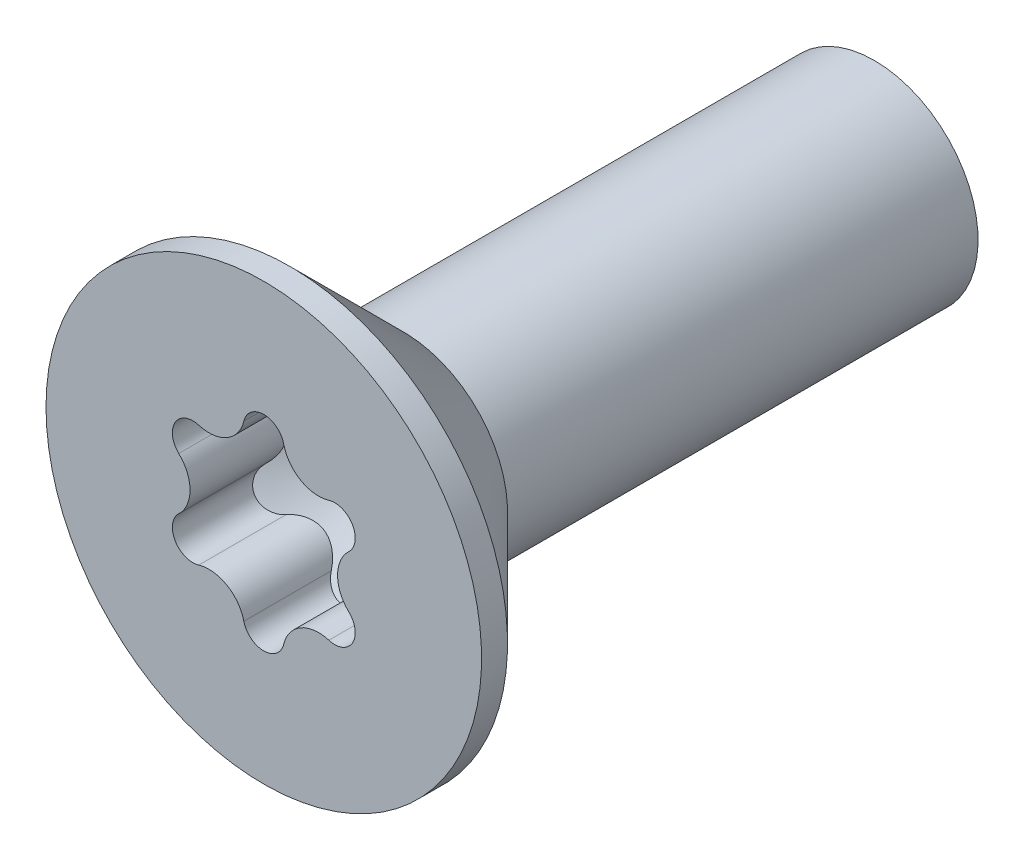
SolidWorks part; units mm, degrees
ref_plane "Front Plane" through (0, 0, 0) normal (0, 0, 1) x (1, 0, 0)
ref_plane "Top Plane" through (0, 0, 0) normal (0, 1, 0) x (1, 0, 0)
ref_plane "Right Plane" through (0, 0, 0) normal (1, 0, 0) x (0, 0, -1)
sketch "BodySke" plane through (0, 0, 0) normal (1, 0, 0) x (0, 0, -1)
  line L0 (0, 0) -> (-1787.2758, 0) construction
  line L1 (0, 0) -> (0, 4.2)
  line L2 (0.5, 4.2) -> (2.7, 2)
  line L3 (0.5, -4.2) -> (2.7, -2) construction
  line L4 (2.7, 2) -> (12, 2)
  line L5 (12, 2) -> (12, 0)
  line L6 (12, 0) -> (0, 0)
  line L7 (0, 0) -> (0, 50000) construction
  line L8 (0.5, 4.2) -> (0, 4.2)
  dimension "D" = 4
  dimension "Dk" = 8.4
  dimension "K" = 2.7
  dimension "L" = 12
  dimension "D1" = 90
  dimension "B" = 12
revolve "Base-Revolve" add sketch "BodySke" angle 360 about L0
cosmetic thread "ThreadCosmetic" [suppressed] parameters "ThdLen"=9.3, "MinorDia"=3.22
sketch "PreBSke" plane through (0, 0, 0) normal (1, 0, 0) x (0, 0, -1)
  line L0 (0, 0) -> (-50000, 0) construction
  line L1 (0, 0) -> (0, 1.975)
  line L2 (0, 4.7) -> (0, -4.7) construction
  line L3 (0, 1.975) -> (1.53, 1.975)
  line L4 (1.53, 1.975) -> (2.7167, 0)
  line L5 (2.7167, 0) -> (0, 0)
  line L6 (1.53, -1.975) -> (2.7167, 0) construction
  dimension "T" = 1.53
  dimension "A" = 3.95
  dimension "D1" = 118
revolve "PreBroach" cut sketch "PreBSke" angle 360 about L0
sketch "HexSke" plane through (0, 0, 0) normal (0, 0, 1) x (1, 0, 0)
  line L0 (0, 0) -> (-43301.2702, 25000) construction
  line L1 (0, 0) -> (-43301.2702, -25000) construction
  line L2 (0, 0) -> (50000, 0) construction
  arc A0 (-1.6394, -0.5027) -> (-1.6394, 0.5027) centre (-2.1139, 0) ccw
  arc A1 (-1.7104, 0.9875) -> (-1.6394, 0.5027) centre (-1.3683, 0.79) ccw
  arc A2 (-1.6394, -0.5027) -> (-1.7104, -0.9875) centre (-1.3683, -0.79) ccw
  arc A3 (-1.2551, 1.1684) -> (-1.7104, 0.9875) centre (-1.3683, 0.79) ccw
  circle A4 centre (0, 0) radius 1.4226 construction
  circle A5 centre (0, 0) radius 1.975 construction
  arc A6 (-1.2551, 1.1684) -> (-0.3843, 1.6711) centre (-1.0569, 1.8307) ccw
  arc A7 (0, 1.975) -> (-0.3843, 1.6711) centre (0, 1.58) ccw
  arc A8 (0.3843, 1.6711) -> (0, 1.975) centre (0, 1.58) ccw
  arc A9 (0.3843, 1.6711) -> (1.2551, 1.1684) centre (1.0569, 1.8307) ccw
  arc A10 (1.7104, 0.9875) -> (1.2551, 1.1684) centre (1.3683, 0.79) ccw
  arc A11 (1.6394, 0.5027) -> (1.7104, 0.9875) centre (1.3683, 0.79) ccw
  arc A12 (1.6394, 0.5027) -> (1.6394, -0.5027) centre (2.1139, 0) ccw
  arc A13 (1.7104, -0.9875) -> (1.6394, -0.5027) centre (1.3683, -0.79) ccw
  arc A14 (1.2551, -1.1684) -> (1.7104, -0.9875) centre (1.3683, -0.79) ccw
  arc A15 (1.2551, -1.1684) -> (0.3843, -1.6711) centre (1.0569, -1.8307) ccw
  arc A16 (0, -1.975) -> (0.3843, -1.6711) centre (0, -1.58) ccw
  arc A17 (-0.3843, -1.6711) -> (0, -1.975) centre (0, -1.58) ccw
  arc A18 (-0.3843, -1.6711) -> (-1.2551, -1.1684) centre (-1.0569, -1.8307) ccw
  arc A19 (-1.7104, -0.9875) -> (-1.2551, -1.1684) centre (-1.3683, -0.79) ccw
  circle A20 centre (0, 0) radius 1.975 construction
  circle A21 centre (0, 0) radius 1.975
  point P56 (0, 0)
  circle M6 centre (0, 0) radius 1.975
  dimension "B" = 2.8452
  dimension "Ri" = 0.395
  dimension "Re" = 0.6913
  dimension "D1" = 60
  dimension "D5" = 6
extrude "Hexalobular" add sketch "HexSke" against normal up to next contours A2 A0 A1 M6 | A7 A3 A6 M6 | A10 A8 A9 M6 | A13 A11 A12 M6 | A16 A14 A15 M6 | A19 A17 A18 M6
sketch "ThdSchSke" plane through (0, 0, 0) normal (1, 0, 0) x (0, 0, -1)
  line L0 (12.2252, 2) -> (12, 1.61)
  line L1 (12, 1.61) -> (11.7748, 2)
  line L2 (11.7748, 2) -> (12.2252, 2)
  line L3 (12, 1.61) -> (12, 2) construction
  line L4 (12, -2) -> (12, 2) construction
  line L5 (12, 2) -> (2.7, 2) construction
  line L6 (0, 0) -> (-50000, 0) construction
  dimension "MinorDia" = 3.22
  dimension "D1" = 60
  dimension "D2" = 0.4503
revolve "ThreadSchematic" cut sketch "ThdSchSke" angle 360 about L6
ref_plane "ThreadPlane" through (0, 0, -2.7) normal (0, 0, -1) x (-1, 0, 0)
pattern_linear "ThdSchPat" [suppressed] count 11
equation "\"MinorDia@ThreadCosmetic\" = \"MinorDia@ThdSchSke\""
equation "\"ThdLen@ThreadCosmetic\" = \"ThreadLength\""
equation "\"Ri@HexSke\"= .1 * \"A@PreBSke\""
equation "\"Re@HexSke\"= .175 * \"A@PreBSke\""
equation "\"ThreadLength\"= IIF ( \"B@BodySke\" = \"L@BodySke\" , \"L@BodySke\" - \"K@BodySke\" , \"B@BodySke\" )"
equation "\"ThdLen@ThreadPlane\"=\"ThreadLength\""
